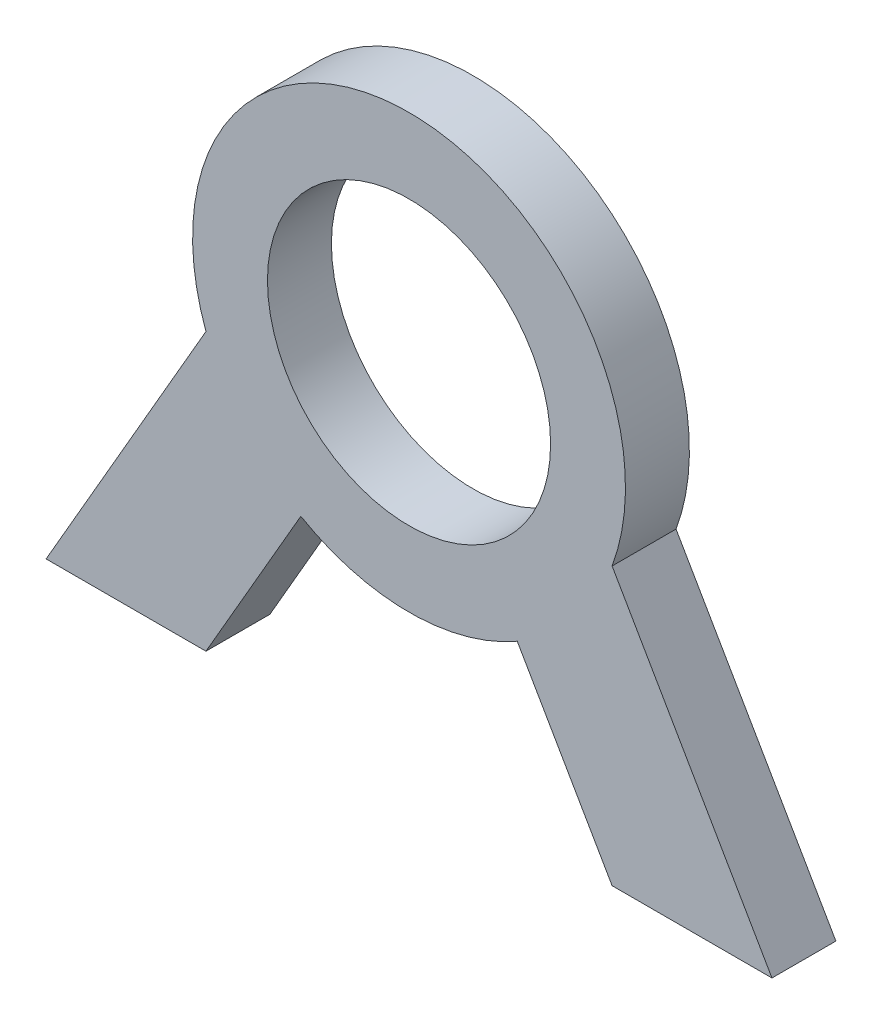
SolidWorks part; units mm, degrees
ref_plane "Front Plane" through (0, 0, 0) normal (0, 0, 1) x (1, 0, 0)
ref_plane "Top Plane" through (0, 0, 0) normal (0, 1, 0) x (1, 0, 0)
ref_plane "Right Plane" through (0, 0, 0) normal (1, 0, 0) x (0, 0, -1)
sketch "Sketch1" plane through (0, 0, 0) normal (0, 0, 1) x (1, 0, 0)
  line L0 (0, 0) -> (0, 27.9451) construction
  line L1 (0, 27.9451) -> (16.1341, 0) construction
  line L2 (0, 27.9451) -> (-16.1341, 0) construction
  line L3 (0, 0) -> (-25.4, 0) construction
  line L4 (0, 0) -> (25.4, 0) construction
  line L5 (-16.1341, 0) -> (-8.5978, 13.0533)
  line L6 (16.1341, 0) -> (8.5978, 13.0533)
  line L7 (-16.1341, 0) -> (-28.8341, 0)
  line L8 (-28.8341, 0) -> (-16.1341, 21.997)
  line L9 (16.1341, 0) -> (28.8341, 0)
  line L10 (28.8341, 0) -> (16.1341, 21.997)
  circle A0 centre (0, 27.9451) radius 11.2471
  arc A1 (-8.5978, 13.0533) -> (8.5978, 13.0533) centre (0, 27.9451) ccw
  arc A2 (16.1341, 21.997) -> (-16.1341, 21.997) centre (0, 27.9451) ccw
  point P15 (-8.5978, 13.0533)
  point P16 (-5.6236, 18.2048)
  point P17 (8.5978, 13.0533)
  dimension "D2" = 12.7
  dimension "D1" = 27.9451
  dimension "D3" = 12.7
extrude "Boss-Extrude2" add sketch "Sketch1" along normal blind 5.08
